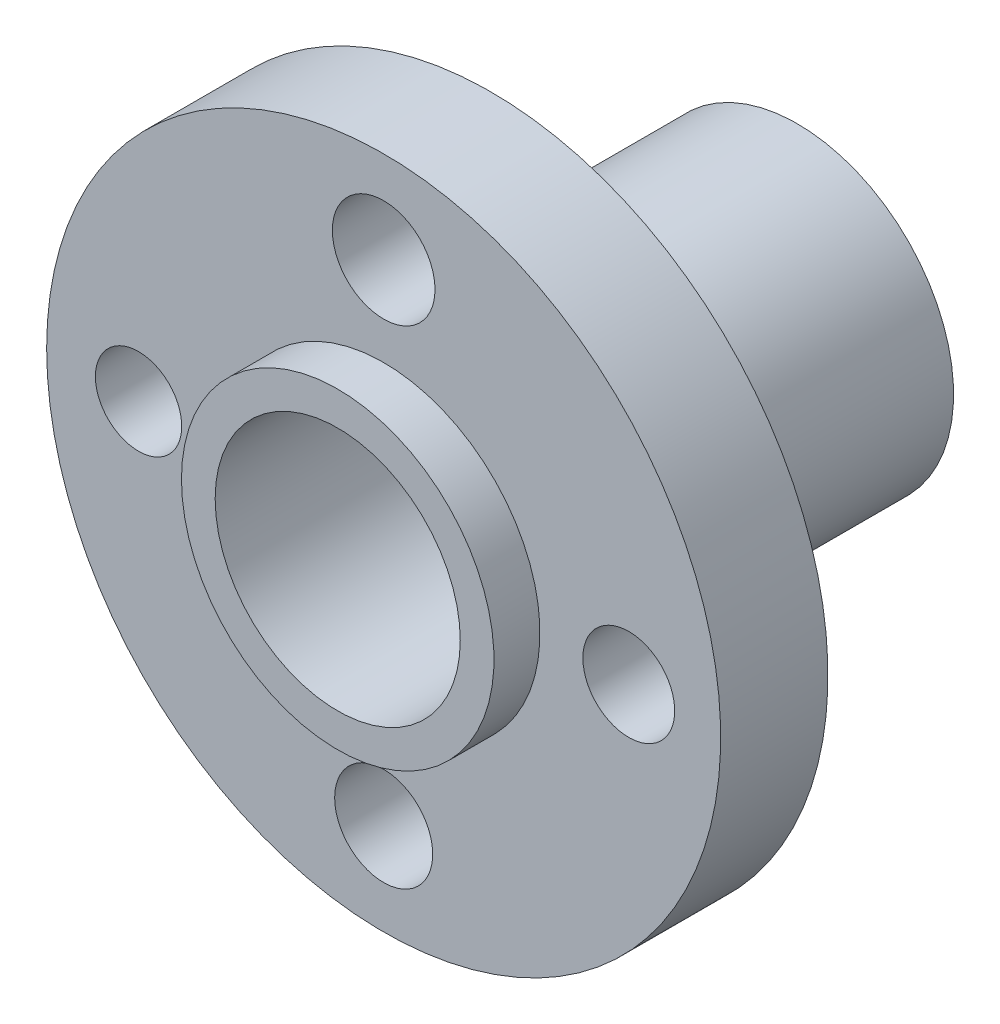
SolidWorks part; units mm, degrees
ref_plane "Front Plane" through (0, 0, 0) normal (0, 0, 1) x (1, 0, 0)
ref_plane "Top Plane" through (0, 0, 0) normal (0, 1, 0) x (1, 0, 0)
ref_plane "Right Plane" through (0, 0, 0) normal (1, 0, 0) x (0, 0, -1)
sketch "Sketch1" plane through (0, 0, 0) normal (0, 1, 0) x (1, 0, 0)
  line L0 (0, 0) -> (5.1, 0)
  line L1 (5.1, 0) -> (5.1, 1.5)
  line L2 (5.1, 1.5) -> (11, 1.5)
  line L3 (11, 1.5) -> (11, 5)
  line L4 (11, 5) -> (5.1, 5)
  line L5 (5.1, 5) -> (5.1, 15)
  line L6 (5.1, 15) -> (0, 15)
  line L7 (0, 15) -> (0, 0)
  dimension "D1" = 1.5
  dimension "D2" = 3.5
  dimension "D3" = 10
  dimension "D4" = 5.1
  dimension "D5" = 11
revolve "Revolve1" add sketch "Sketch1" angle 360 about L7
sketch "Sketch2" plane through (0, 0, -15) normal (0, 0, -1) x (-1, 0, 0)
  circle A0 centre (0, 0) radius 4
  dimension "D1" = 8
extrude "Cut-Extrude1" cut sketch "Sketch2" against normal through all
sketch "Sketch3" plane through (0, 0, -5) normal (0, 0, -1) x (-1, 0, 0)
  circle A0 centre (8, 0) radius 1.4091
  circle A1 centre (0, -8) radius 1.6
  circle A2 centre (-8, 0) radius 1.4985
  circle A3 centre (0, 8) radius 1.6743
  dimension "D1" = 3.2
  dimension "D2" = 8
  dimension "D3" = 8
  dimension "D4" = 8
  dimension "D5" = 8
extrude "Cut-Extrude2" cut sketch "Sketch3" against normal through all
